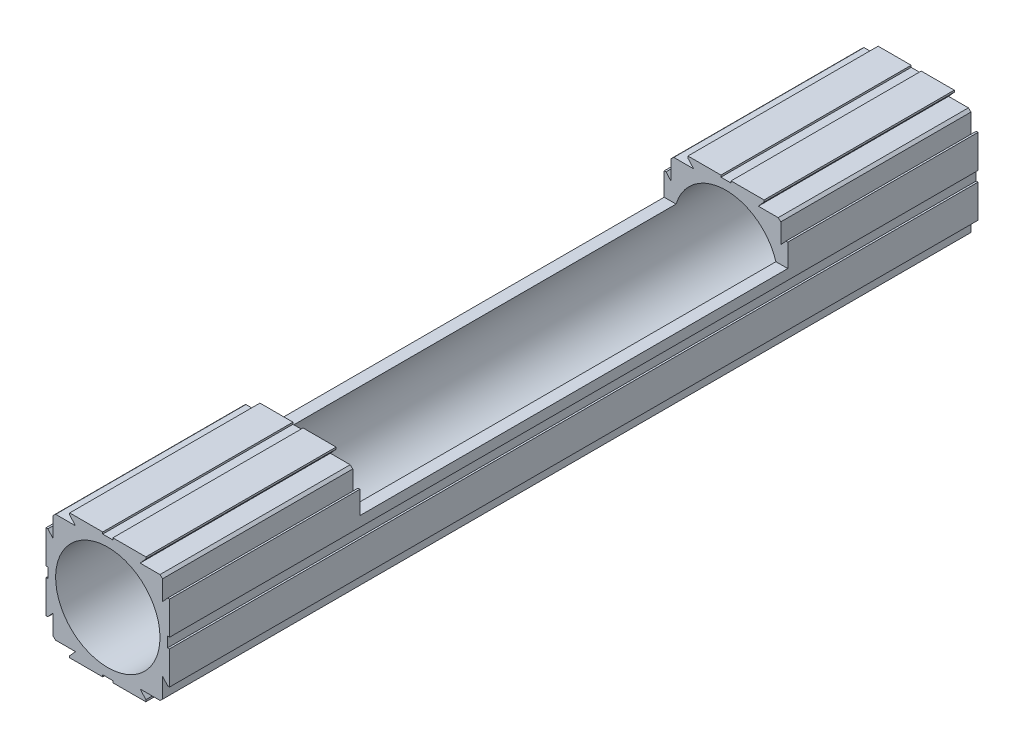
SolidWorks part; units mm, degrees
ref_plane "Front Plane" through (0, 0, 0) normal (0, 0, 1) x (1, 0, 0)
ref_plane "Top Plane" through (0, 0, 0) normal (0, 1, 0) x (1, 0, 0)
ref_plane "Right Plane" through (0, 0, 0) normal (1, 0, 0) x (0, 0, -1)
sketch "Sketch2" plane through (0, 0, 0) normal (0, 0, 1) x (1, 0, 0)
  line L0 (-20.338, 33.5291) -> (-2.6993, 33.5291)
  line L1 (-2.6993, 33.5291) -> (-2.6993, 32.5352)
  line L2 (-2.6993, 32.5352) -> (2.6993, 32.5352)
  line L3 (-20.338, 33.5291) -> (-20.338, 32.5352)
  line L4 (-20.338, 32.5352) -> (-17.2715, 29.113)
  line L5 (-17.2715, 29.113) -> (-27.8712, 29.113)
  line L6 (-27.8712, 29.113) -> (-29.2621, 27.8667)
  line L7 (-29.2621, 27.8667) -> (-29.2621, 17.267)
  line L8 (-29.2621, 17.267) -> (-32.0139, 20.338)
  line L9 (-32.0139, 20.338) -> (-33.0078, 20.338)
  line L10 (-33.0078, 20.338) -> (-33.0078, 2.6993)
  line L11 (-33.0078, 2.6993) -> (-32.0139, 2.6993)
  line L12 (-32.0139, 2.6993) -> (-32.0139, -2.6993)
  line L13 (-32.0139, 0) -> (0, 0) construction
  line L14 (0, 0) -> (0, 32.5352) construction
  line L15 (32.0139, 2.6993) -> (32.0139, -2.6993)
  line L16 (33.0078, 2.6993) -> (32.0139, 2.6993)
  line L17 (33.0078, 20.338) -> (33.0078, 2.6993)
  line L18 (32.0139, 20.338) -> (33.0078, 20.338)
  line L19 (29.2621, 17.267) -> (32.0139, 20.338)
  line L20 (29.2621, 27.8667) -> (29.2621, 17.267)
  line L21 (27.8712, 29.113) -> (29.2621, 27.8667)
  line L22 (17.2715, 29.113) -> (27.8712, 29.113)
  line L23 (20.338, 32.5352) -> (17.2715, 29.113)
  line L24 (20.338, 33.5291) -> (20.338, 32.5352)
  line L25 (2.6993, 33.5291) -> (2.6993, 32.5352)
  line L26 (20.338, 33.5291) -> (2.6993, 33.5291)
  line L27 (20.338, -33.5291) -> (2.6993, -33.5291)
  line L28 (2.6993, -33.5291) -> (2.6993, -32.5352)
  line L29 (20.338, -33.5291) -> (20.338, -32.5352)
  line L30 (20.338, -32.5352) -> (17.2715, -29.113)
  line L31 (17.2715, -29.113) -> (27.8712, -29.113)
  line L32 (27.8712, -29.113) -> (29.2621, -27.8667)
  line L33 (29.2621, -27.8667) -> (29.2621, -17.267)
  line L34 (29.2621, -17.267) -> (32.0139, -20.338)
  line L35 (32.0139, -20.338) -> (33.0078, -20.338)
  line L36 (33.0078, -20.338) -> (33.0078, -2.6993)
  line L37 (33.0078, -2.6993) -> (32.0139, -2.6993)
  line L38 (-33.0078, -2.6993) -> (-32.0139, -2.6993)
  line L39 (-33.0078, -20.338) -> (-33.0078, -2.6993)
  line L40 (-32.0139, -20.338) -> (-33.0078, -20.338)
  line L41 (-29.2621, -17.267) -> (-32.0139, -20.338)
  line L42 (-29.2621, -27.8667) -> (-29.2621, -17.267)
  line L43 (-27.8712, -29.113) -> (-29.2621, -27.8667)
  line L44 (-17.2715, -29.113) -> (-27.8712, -29.113)
  line L45 (-20.338, -32.5352) -> (-17.2715, -29.113)
  line L46 (-20.338, -33.5291) -> (-20.338, -32.5352)
  line L47 (-2.6993, -32.5352) -> (2.6993, -32.5352)
  line L48 (-2.6993, -33.5291) -> (-2.6993, -32.5352)
  line L49 (-20.338, -33.5291) -> (-2.6993, -33.5291)
  circle A0 centre (0, 0) radius 27.8739
  point P40 (32.0139, 0)
  dimension "D5" = 41.862
extrude "Boss-Extrude1" add sketch "Sketch2" along normal blind 500
sketch "Sketch3" plane through (29.2621, 0, 0) normal (1, 0, 0) x (0, 0, -1)
  line L0 (-500, 33.5291) -> (0, 33.5291) construction
  line L1 (-398.4, 33.5291) -> (-169.8, 33.5291)
  line L2 (-398.4, 33.5291) -> (-398.4, 8.1291)
  line L3 (-398.4, 8.1291) -> (-169.8, 8.1291)
  line L4 (-169.8, 33.5291) -> (-169.8, 8.1291)
  line L5 (-500, 17.267) -> (-500, 27.8667) construction
  line L6 (-500, -33.5291) -> (0, -33.5291) construction
  line L7 (-68.2, 33.5291) -> (0, 33.5291)
  line L8 (-68.2, 33.5291) -> (-68.2, -33.5291)
  line L9 (-68.2, -33.5291) -> (0, -33.5291)
  line L10 (0, 33.5291) -> (0, -33.5291)
  line L11 (-500, -20.338) -> (-500, -2.6993) construction
  dimension "D1" = 25.4
  dimension "D2" = 101.6
  dimension "D3" = 228.6
  dimension "D4" = 431.8
extrude "Cut-Extrude1" cut sketch "Sketch3" against normal through all both and the other way through all
